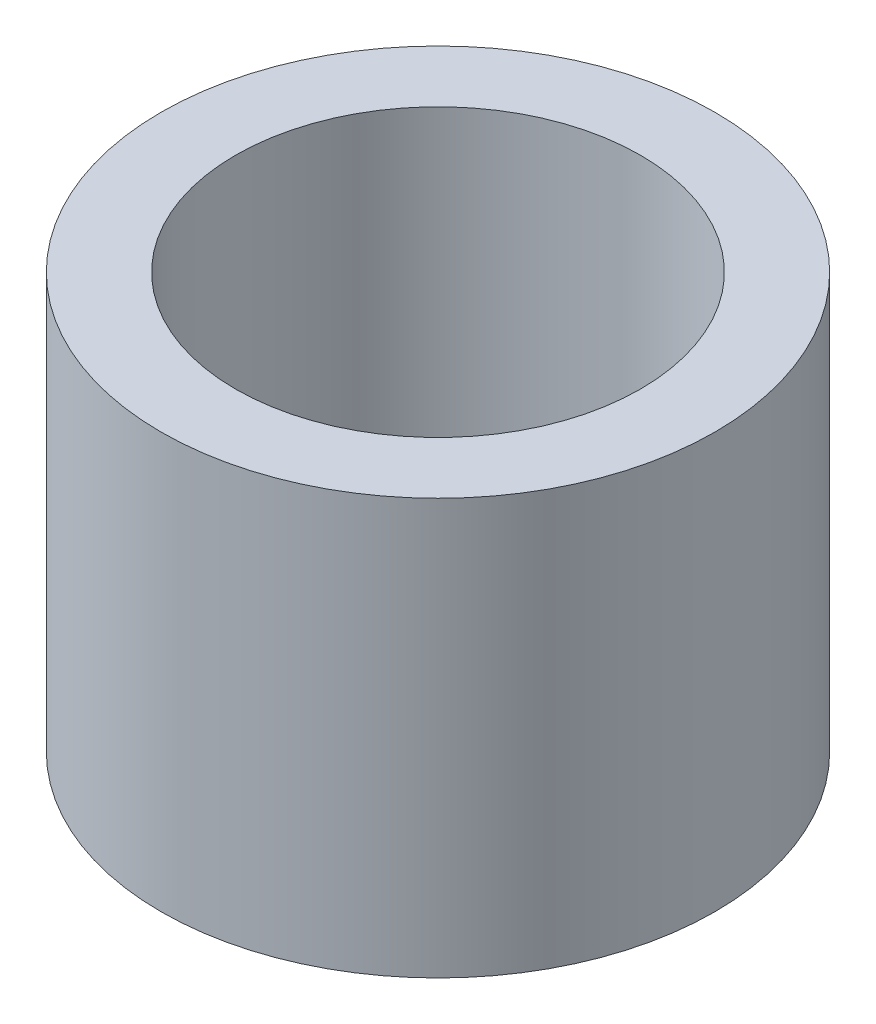
SolidWorks part; units mm, degrees
ref_plane "Front" through (0, 0, 0) normal (0, 0, 1) x (1, 0, 0)
ref_plane "Top" through (0, 0, 0) normal (0, 1, 0) x (1, 0, 0)
ref_plane "Right" through (0, 0, 0) normal (1, 0, 0) x (0, 0, -1)
sketch "Sketch1" plane through (0, 0, 0) normal (0, 1, 0) x (1, 0, 0)
  circle A0 centre (0, 0) radius 4
  dimension "D1" = 8
extrude "Boss-Extrude1" add sketch "Sketch1" along normal blind 6
sketch "Sketch2" plane through (0, 6, 0) normal (0, 1, 0) x (1, 0, 0)
  circle A0 centre (0, 0) radius 2.925
  dimension "D1" = 5.85
extrude "Cut-Extrude1" cut sketch "Sketch2" against normal blind 10
